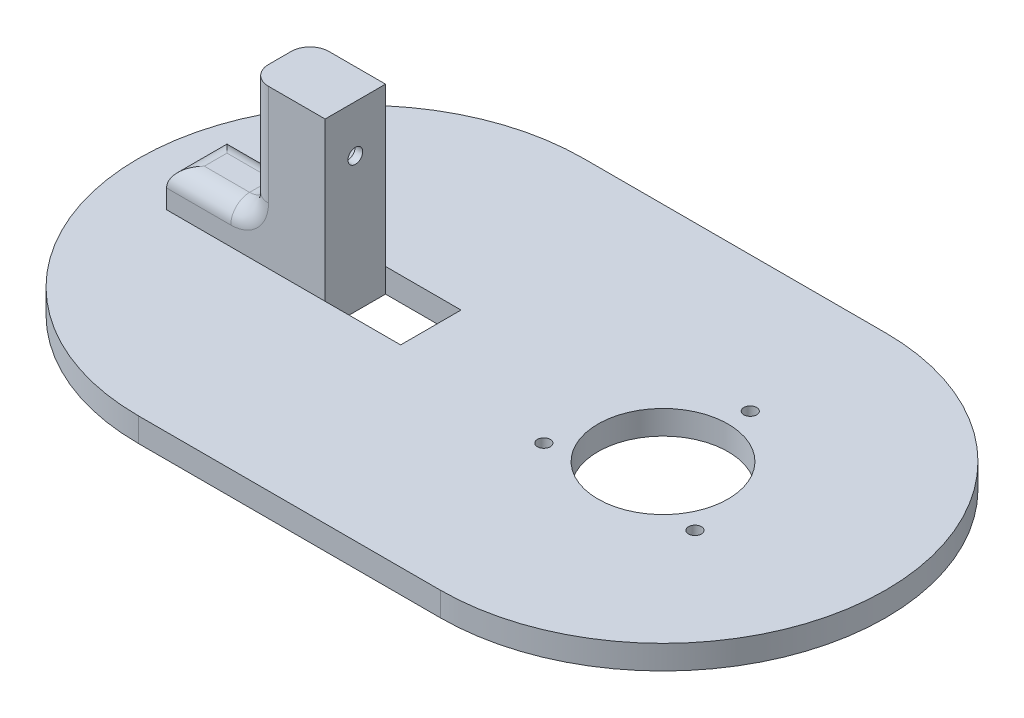
SolidWorks part; units mm, degrees
ref_plane "Plan de face" through (0, 0, 0) normal (0, 0, 1) x (1, 0, 0)
ref_plane "Plan de dessus" through (0, 0, 0) normal (0, 1, 0) x (1, 0, 0)
ref_plane "Plan de droite" through (0, 0, 0) normal (1, 0, 0) x (0, 0, -1)
sketch "Esquisse1" plane through (0, 0, 0) normal (0, 1, 0) x (1, 0, 0)
  line L0 (-40, 0) -> (40, 0) construction
  line L1 (-40, 59) -> (40, 59)
  line L2 (-40, -59) -> (40, -59)
  arc A0 (-40, 59) -> (-40, -59) centre (-40, 0) ccw
  arc A1 (40, -59) -> (40, 59) centre (40, 0) ccw
  point P3 (0, 0)
  dimension "D2" = 59
  dimension "D1" = 80
extrude "Boss.-Extru.1" add sketch "Esquisse1" along normal mid plane 6.35
sketch "Esquisse3" plane through (0, 0, 0) normal (0, 1, 0) x (1, 0, 0)
  line L0 (-83.5, 8) -> (-41.5, -8) construction
  line L1 (-83.5, 8) -> (-41.5, 8)
  line L2 (-83.5, 8) -> (-83.5, -8)
  line L3 (-83.5, -8) -> (-41.5, -8)
  line L4 (-41.5, 8) -> (-41.5, -8)
  line L5 (-83.5, -8) -> (-41.5, 8) construction
  point P4 (-62.5, 0)
  dimension "D1" = 42
  dimension "D2" = 16
  dimension "D3" = 41.5
extrude "Boss.-Extru.2" add sketch "Esquisse3" along normal blind 45
sketch "Esquisse4" plane through (0, 3.175, 0) normal (0, 1, 0) x (1, 0, 0)
  line L0 (-41.5, -8) -> (-83.5, -8) construction
  line L1 (-41.5, 8) -> (-21.5, 8)
  line L2 (-41.5, 8) -> (-41.5, -8)
  line L3 (-41.5, -8) -> (-21.5, -8)
  line L4 (-21.5, 8) -> (-21.5, -8)
  dimension "D1" = 20
extrude "Enlèv. mat.-Extru.1" cut sketch "Esquisse4" against normal through all contours L1 L4 L3 L2
sketch "Esquisse5" plane through (0, 0, 8) normal (0, 0, 1) x (1, 0, 0)
  line L0 (-41.5, 45) -> (-41.5, 3.175) construction
  line L1 (-83.5, 45) -> (-61.5, 45)
  line L2 (-83.5, 45) -> (-83.5, 13.175)
  line L3 (-83.5, 13.175) -> (-61.5, 13.175)
  line L4 (-61.5, 45) -> (-61.5, 13.175)
  line L5 (-41.5, 3.175) -> (-83.5, 3.175) construction
  dimension "D1" = 20
  dimension "D2" = 10
extrude "Enlèv. mat.-Extru.2" cut sketch "Esquisse5" against normal through all contours L3 L4 L1 L2
fillet "Congé1" radius 5 6 edges at (-61.5, 29.0875, -8) (-61.5, 29.0875, 8) (-72.5, 13.175, -8) (-72.5, 13.175, 8) (-83.5, 13.175, 0) (-61.5, 13.175, 0)
hole_wizard "Dégagement M3.51" positions "Esquisse6" profile "Esquisse7" hole size "M3.5" standard "Ansi Metric" end condition through all
sketch "Esquisse6" plane through (-41.5, 0, 0) normal (1, 0, 0) x (0, 0, -1)
  point P0 (0, 32.55)
  dimension "D1" = 32.55
sketch "Esquisse7" plane through (-41.5, 32.55, 0) normal (0, 1, 0) x (0, 0, -1)
  line L0 (0, 0) -> (0, 57.5)
  line L1 (0, 57.5) -> (1.95, 57.5)
  line L2 (1.95, 57.5) -> (1.95, 0)
  line L5 (1.95, 0) -> (0, 0)
  line L11 (0, -6.35) -> (0, 107.95) construction
  dimension "Diamètre du perçage jusqu'au prochain" = 3.9
  dimension "Profondeur du perçage jusqu'au prochain" = 57.5
hole_wizard "Dégagement M31" positions "Esquisse10" profile "Esquisse9" hole size "M3" standard "Ansi Metric" end condition through all
sketch "Esquisse10" plane through (0, 3.175, 0) normal (0, 1, 0) x (1, 0, 0)
  line L0 (40, 0) -> (40, 23.1125) construction
  line L2 (40, 0) -> (19.984, -11.5563) construction
  line L4 (40, 0) -> (60.016, -11.5563) construction
  point P22 (40, 23.1125)
  point P35 (19.984, -11.5563)
  point P38 (60.016, -11.5563)
  dimension "D1" = 23.1125
  dimension "D2" = 120
  dimension "D3" = 120
sketch "Esquisse9" plane through (60.016, 3.175, 11.5563) normal (1, 0, 0) x (0, 0, 1)
  line L0 (0, 0) -> (0, 6.35)
  line L1 (0, 6.35) -> (1.7, 6.35)
  line L2 (1.7, 6.35) -> (1.7, 0)
  line L5 (1.7, 0) -> (0, 0)
  line L11 (0, -6.35) -> (0, 107.95) construction
  dimension "Diamètre du perçage jusqu'au prochain" = 3.4
  dimension "Profondeur du perçage jusqu'au prochain" = 6.35
sketch "Esquisse11" plane through (0, 3.175, 0) normal (0, 1, 0) x (1, 0, 0)
  circle A0 centre (40, 0) radius 17.225
  arc A1 (40, -59) -> (40, 59) centre (40, 0) ccw construction
  dimension "D1" = 34.45
extrude "Enlèv. mat.-Extru.3" cut sketch "Esquisse11" against normal through all
hole_wizard "Diamètre du perçage Ø4.5 (4.5)2" positions "Esquisse12" profile "Esquisse13" hole size "Ø4.5" standard "Ansi Metric"
sketch "Esquisse12" plane through (0, -3.175, 0) normal (0, -1, 0) x (-1, 0, 0)
  line L0 (83.5, -8) -> (83.5, 8) construction
  line L2 (61.5, 3) -> (61.5, -3) construction
  point P0 (78.5, 0)
  point P2 (66.5, 0)
  dimension "D1" = 5
  dimension "D2" = 5
sketch "Esquisse13" plane through (-78.5, -3.175, 0) normal (1, 0, 0) x (0, 0, -1)
  line L0 (0, 0) -> (0, 5.8)
  line L1 (0, 5.8) -> (2.25, 5.8)
  line L2 (2.25, 5.8) -> (2.25, 0)
  line L5 (2.25, 0) -> (0, 0)
  line L10 (0, 5.8) -> (-2.25, 5.8) construction
  line L11 (0, -6.35) -> (0, 107.95) construction
  dimension "Diamètre du perçage" = 4.5
  dimension "Profondeur du perçage" = 5.8
  dimension "Angle de pointe" = 180
sketch "Esquisse14" plane through (-61.5, 0, 0) normal (-1, 0, 0) x (0, 0, 1)
  line L1 (4.6765, 32.55) -> (2.3383, 36.6)
  line L2 (2.3383, 36.6) -> (-2.3383, 36.6)
  line L3 (-2.3383, 36.6) -> (-4.6765, 32.55)
  line L4 (-4.6765, 32.55) -> (-2.3383, 28.5)
  line L5 (-2.3383, 28.5) -> (2.3383, 28.5)
  line L6 (2.3383, 28.5) -> (4.6765, 32.55)
  circle A0 centre (0, 32.55) radius 4.05 construction
  dimension "D1" = 8.1
extrude "Enlèv. mat.-Extru.4" cut sketch "Esquisse14" against normal blind 18
